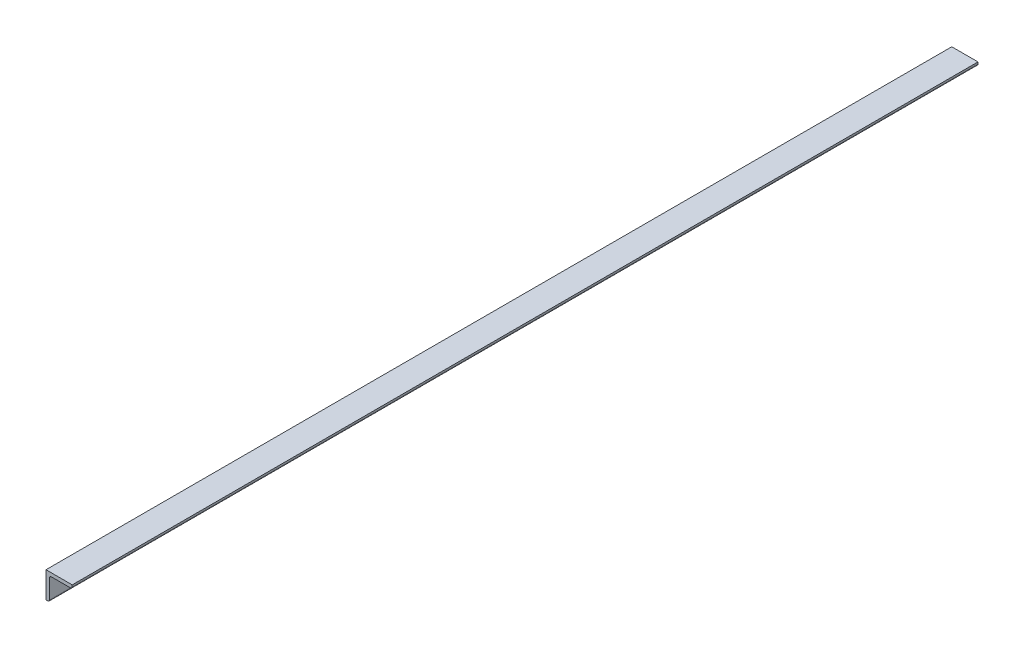
SolidWorks part; units mm, degrees
material "ASTM A36 Steel"
ref_plane "Front Plane" through (0, 0, 0) normal (0, 0, 1) x (1, 0, 0)
ref_plane "Top Plane" through (0, 0, 0) normal (0, 1, 0) x (1, 0, 0)
ref_plane "Right Plane" through (0, 0, 0) normal (1, 0, 0) x (0, 0, -1)
sketch "Sketch1" plane through (0, 0, 0) normal (0, 0, 1) x (1, 0, 0)
  line L0 (-8.625, 38.8125) -> (-38.625, 38.8125)
  line L1 (-38.625, 38.8125) -> (-38.625, 8.8125)
  line L2 (-38.625, 8.8125) -> (-36.625, 8.8125)
  line L3 (-34.625, 10.8125) -> (-34.625, 32.8125)
  line L4 (-32.625, 34.8125) -> (-10.625, 34.8125)
  line L5 (-8.625, 36.8125) -> (-8.625, 38.8125)
  arc A0 (-36.625, 8.8125) -> (-34.625, 10.8125) centre (-36.625, 10.8125) ccw
  arc A1 (-10.625, 34.8125) -> (-8.625, 36.8125) centre (-10.625, 36.8125) ccw
  arc A2 (-34.625, 32.8125) -> (-32.625, 34.8125) centre (-32.625, 32.8125) cw
  point P8 (-34.625, 8.8125)
  point P11 (-8.625, 34.8125)
  dimension "D5" = 2
  dimension "D1" = 30
  dimension "D2" = 30
  dimension "D3" = 4
  dimension "D4" = 4
extrude "Boss-Extrude1" add sketch "Sketch1" along normal blind 1036
